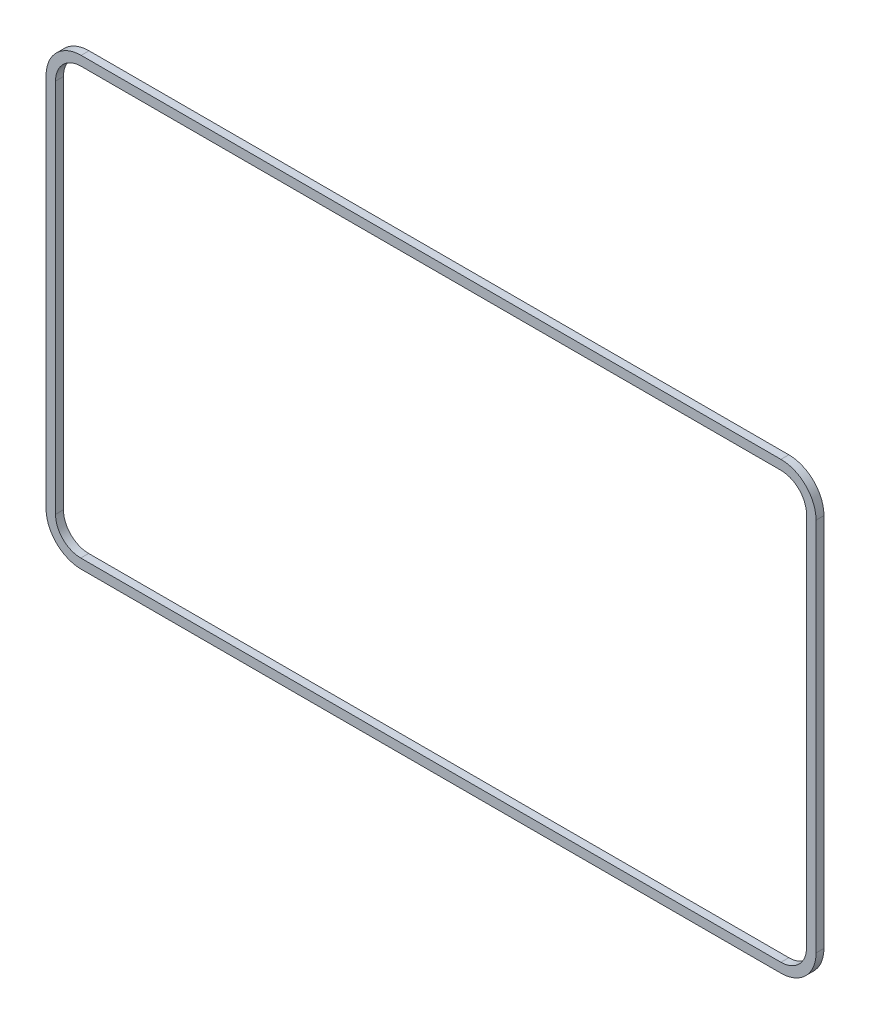
SolidWorks part; units mm, degrees
ref_plane "Front Plane" through (0, 0, 0) normal (0, 0, 1) x (1, 0, 0)
ref_plane "Top Plane" through (0, 0, 0) normal (0, 1, 0) x (1, 0, 0)
ref_plane "Right Plane" through (0, 0, 0) normal (1, 0, 0) x (0, 0, -1)
sketch "Sketch1" plane through (0, 0, 0) normal (0, 0, 1) x (1, 0, 0)
  line L0 (0, 56.28) -> (0, 56.38) construction
  line L1 (88.5, -56.28) -> (-88.5, -56.28)
  line L2 (97.38, -47.4) -> (97.38, 47.4)
  line L3 (88.5, 56.28) -> (-88.5, 56.28)
  line L4 (-97.38, -47.4) -> (-97.38, 47.4)
  line L5 (97.38, -56.28) -> (-97.38, 56.28) construction
  line L6 (97.38, 56.28) -> (-97.38, -56.28) construction
  line L7 (-88.6, 56.38) -> (88.6, 56.38) construction
  line L8 (97.38, 0) -> (97.48, 0) construction
  line L9 (97.48, 47.5) -> (97.48, -47.5) construction
  line L10 (0, 53.88) -> (0, 56.28) construction
  line L11 (88.5, -53.88) -> (-88.6, -53.88)
  line L12 (94.98, -47.4) -> (94.98, 47.4)
  line L13 (88.5, 53.88) -> (-88.5, 53.88)
  line L14 (-94.98, -47.5) -> (-94.98, 47.4)
  line L15 (94.98, -53.88) -> (-94.98, 53.88) construction
  line L16 (94.98, 53.88) -> (-94.98, -53.88) construction
  line L17 (94.98, 0) -> (97.38, 0) construction
  line L18 (0, 53.88) -> (0, 53.38) construction
  line L19 (-88.6, 53.38) -> (88.6, 53.38) construction
  arc A0 (97.38, -47.4) -> (88.5, -56.28) centre (88.5, -47.4) cw
  arc A1 (88.5, 56.28) -> (97.38, 47.4) centre (88.5, 47.4) cw
  arc A2 (-88.5, -56.28) -> (-97.38, -47.4) centre (-88.5, -47.4) cw
  arc A3 (-97.38, 47.4) -> (-88.5, 56.28) centre (-88.5, 47.4) cw
  arc A4 (-88.6, 56.38) -> (-97.48, 47.5) centre (-88.6, 47.5) ccw construction
  arc A5 (-97.48, -47.5) -> (-88.6, -56.38) centre (-88.6, -47.5) ccw construction
  arc A6 (88.6, -56.38) -> (97.48, -47.5) centre (88.6, -47.5) ccw construction
  arc A7 (97.48, 47.5) -> (88.6, 56.38) centre (88.6, 47.5) ccw construction
  arc A8 (-94.48, -47.5) -> (-88.6, -53.38) centre (-88.6, -47.5) ccw construction
  arc A11 (94.98, -47.4) -> (88.5, -53.88) centre (88.5, -47.4) cw
  arc A12 (88.5, 53.88) -> (94.98, 47.4) centre (88.5, 47.4) cw
  arc A13 (-88.6, -53.88) -> (-94.98, -47.5) centre (-88.6, -47.5) cw
  arc A14 (-94.98, 47.4) -> (-88.5, 53.88) centre (-88.5, 47.4) cw
  point P0 (0, 0)
  point P38 (0, 0)
  dimension "D1" = 0.1
  dimension "D2" = 0.5
extrude "Boss-Extrude1" add sketch "Sketch1" along normal blind 2
